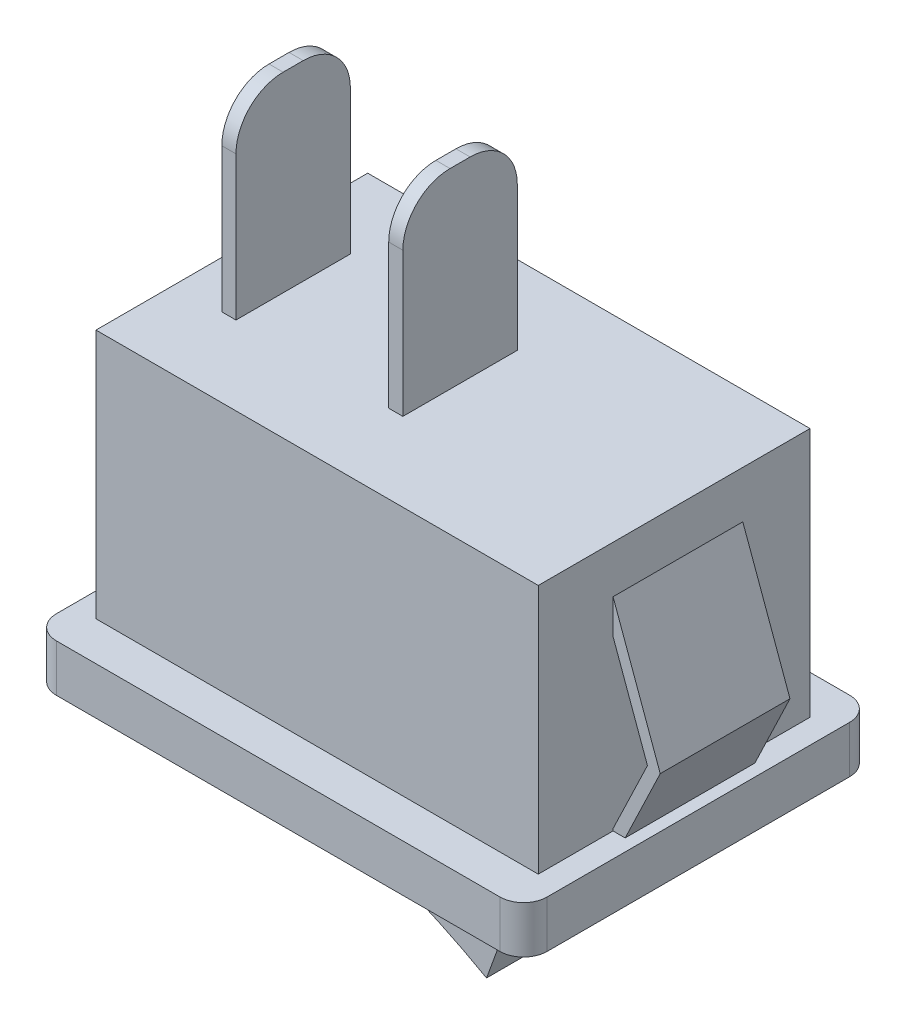
SolidWorks part; units mm, degrees
ref_plane "Front Plane" through (0, 0, 0) normal (0, 0, 1) x (1, 0, 0)
ref_plane "Top Plane" through (0, 0, 0) normal (0, 1, 0) x (1, 0, 0)
ref_plane "Right Plane" through (0, 0, 0) normal (1, 0, 0) x (0, 0, -1)
sketch "Sketch1" plane through (0, 0, 0) normal (0, 1, 0) x (1, 0, 0)
  line L1 (-9.375, -5.76) -> (9.375, -5.76)
  line L2 (-9.375, -5.76) -> (-9.375, 5.76)
  line L3 (-9.375, 5.76) -> (9.375, 5.76)
  line L4 (9.375, -5.76) -> (9.375, 5.76)
  line L5 (-9.375, -5.76) -> (9.375, 5.76) construction
  line L6 (-9.375, 5.76) -> (9.375, -5.76) construction
  point P0 (0, 0)
  dimension "D1" = 11.52
  dimension "D2" = 18.75
extrude "Boss-Extrude1" add sketch "Sketch1" along normal blind 10.6
sketch "Sketch2" plane through (0, 0, 0) normal (0, 1, 0) x (1, 0, 0)
  line L1 (-10.4, 7.41) -> (10.4, 7.41)
  line L2 (-10.4, 7.41) -> (-10.4, -7.41)
  line L3 (-10.4, -7.41) -> (10.4, -7.41)
  line L4 (10.4, 7.41) -> (10.4, -7.41)
  line L5 (-10.4, 7.41) -> (10.4, -7.41) construction
  line L6 (-10.4, -7.41) -> (10.4, 7.41) construction
  point P0 (0, 0)
  dimension "D1" = 20.8
  dimension "D2" = 14.82
extrude "Boss-Extrude2" add sketch "Sketch2" against normal blind 2
sketch "Sketch4" plane through (0, 0, 7.41) normal (0, 0, 1) x (1, 0, 0)
  line L0 (7.7, -2) -> (-7.7, -2)
  line L1 (-10.4, -2) -> (10.4, -2) construction
  line L2 (7.7, -2) -> (6.3319, -5.7588)
  line L3 (7.7, -2) -> (7.7, -5.7588) construction
  line L4 (10.4, -2) -> (10.4, 0) construction
  line L5 (-10.4, -2) -> (-10.4, 0) construction
  spline S0 degree 2 poles (-7.7, -2) (-0.3643, -2.0172) (6.3319, -5.7588) knots 0 0 0 1 1 1
  dimension "D5" = 14.6876
  dimension "D1" = 20
  dimension "D2" = 4
  dimension "D3" = 2.7
  dimension "D4" = 2.7
extrude "Boss-Extrude3" add sketch "Sketch4" against normal blind 9.6 from offset 2.5 offset against normal yes
sketch "Sketch5" plane through (0, 10.6, 0) normal (0, 1, 0) x (1, 0, 0)
  line L0 (0, 0) -> (-9.375, 0) construction
  line L1 (-9.375, 5.76) -> (-9.375, -5.76) construction
  line L3 (-7.375, -2.425) -> (-6.775, -2.425)
  line L4 (-7.375, -2.425) -> (-7.375, 2.425)
  line L5 (-7.375, 2.425) -> (-6.775, 2.425)
  line L6 (-6.775, -2.425) -> (-6.775, 2.425)
  line L7 (-7.375, -2.425) -> (-6.775, 2.425) construction
  line L8 (-7.375, 2.425) -> (-6.775, -2.425) construction
  line L9 (-0.3, -2.425) -> (0.3, -2.425)
  line L10 (-0.3, -2.425) -> (-0.3, 2.425)
  line L11 (-0.3, 2.425) -> (0.3, 2.425)
  line L12 (0.3, -2.425) -> (0.3, 2.425)
  line L13 (-0.3, -2.425) -> (0.3, 2.425) construction
  line L14 (-0.3, 2.425) -> (0.3, -2.425) construction
  point P5 (-7.075, 0)
  dimension "D1" = 4.85
  dimension "D2" = 0.6
  dimension "D3" = 2
extrude "Boss-Extrude4" add sketch "Sketch5" along normal blind 8.1
sketch "Sketch6" plane through (0, 0, -5.76) normal (0, 0, -1) x (-1, 0, 0)
  line L0 (9.375, 8.6) -> (11.375, 3.105)
  line L1 (9.375, 10.6) -> (9.375, 0) construction
  line L2 (11.375, 3.105) -> (9.8875, 0)
  line L3 (-10.4, 0) -> (10.4, 0) construction
  line L4 (10.4, 0) -> (9.375, 0) construction
  line L5 (8.9052, 8.429) -> (10.8333, 3.1315)
  line L6 (10.8333, 3.1315) -> (9.4366, 0.216)
  line L7 (9.4366, 0.216) -> (9.3331, 0)
  line L8 (9.375, 7.1381) -> (10.8333, 3.1315)
  point P11 (9.375, 7.1381)
  point P12 (9.8875, 0)
  line M4 (9.375, 0) -> (9.375, 10.6)
  dimension "D1" = 20
  dimension "D2" = 2
  dimension "D3" = 2
  dimension "D4" = 0.5
extrude "Boss-Extrude5" add sketch "Sketch6" against normal blind 5.5 from offset 2.85 contours L4 L2 L0 L5 L6 L7 M4 offset against normal yes
mirror "Mirror1" about plane through (0, 0, 0) normal (1, 0, 0) of "Boss-Extrude5"
fillet "Fillet1" radius 2 4 edges at (0, 18.7, -2.425) (0, 18.7, 2.425) (-7.075, 18.7, 2.425) (-7.075, 18.7, -2.425)
fillet "Fillet2" radius 1 4 edges at (10.4, -1, 7.41) (10.4, -1, -7.41) (-10.4, -1, 7.41) (-10.4, -1, -7.41)
